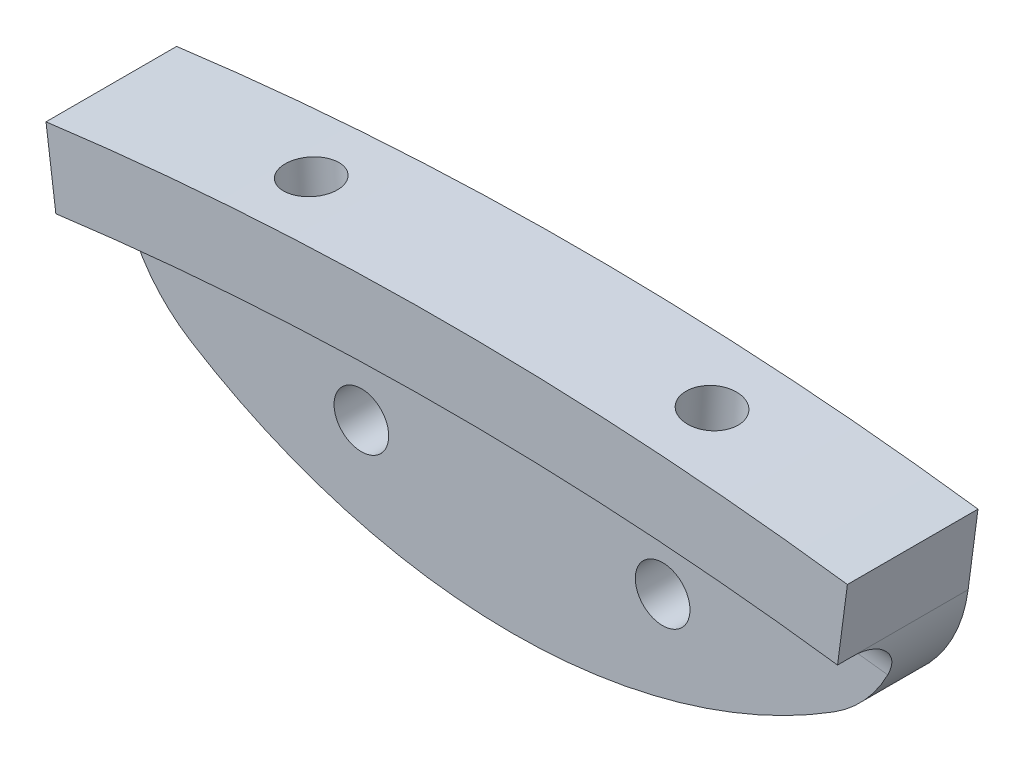
SolidWorks part; units mm, degrees
ref_plane "Front Plane" through (0, 0, 0) normal (0, 0, 1) x (1, 0, 0)
ref_plane "Top Plane" through (0, 0, 0) normal (0, 1, 0) x (1, 0, 0)
ref_plane "Right Plane" through (0, 0, 0) normal (1, 0, 0) x (0, 0, -1)
sketch "Sketch1" plane through (0, 0, 0) normal (0, 0, 1) x (1, 0, 0)
  line L0 (0, 0) -> (0, 193.675) construction
  line L1 (15.875, 0) -> (15.875, 193.675) construction
  line L2 (-15.875, 0) -> (-15.875, 193.675) construction
  line L3 (-25.3273, 192.0118) -> (-24.7044, 187.2902)
  line L4 (25.3273, 192.0118) -> (24.7044, 187.2902)
  line L5 (0, 188.9125) -> (0, 174.625) construction
  circle A0 centre (0, 0) radius 193.675 construction
  arc A1 (-25.3273, 192.0118) -> (25.3273, 192.0118) centre (0, 0) cw
  circle A2 centre (-9.5206, 181.5192) radius 1.7272
  circle A3 centre (9.5206, 181.5192) radius 1.7272
  arc A4 (-98.5088, 144.1871) -> (114.5348, 131.8168) centre (0, 0) cw construction
  arc A5 (-24.7044, 187.2902) -> (24.7044, 187.2902) centre (0, 0) cw construction
  arc A6 (-20.3182, 180.4641) -> (20.3182, 180.4641) centre (0, 212.8951) ccw
  arc A7 (-24.7044, 187.2902) -> (-20.3182, 180.4641) centre (-15.2612, 188.5358) ccw
  arc A8 (24.7044, 187.2902) -> (20.3182, 180.4641) centre (15.2612, 188.5358) cw
  arc A10 (-9.5206, 181.5192) -> (9.5206, 181.5192) centre (0, 0) cw construction
  point P19 (0, 181.7687)
  point P27 (-10.5513, 180.4641)
  dimension "D1" = 387.35
  dimension "D3" = 3.4544
  dimension "D4" = 19.05
  dimension "D7" = 4.7625
  dimension "D8" = 9.525
  dimension "D9" = 19.05
  dimension "D10" = 181.7687
  dimension "D2" = 50.8
  dimension "D5" = 15.875
  dimension "D6" = 15.875
extrude "Boss-Extrude1" add sketch "Sketch1" along normal blind 4.1275
sketch "Sketch2" plane through (0, 0, 4.1275) normal (0, 0, 1) x (1, 0, 0)
  line L0 (24.7044, 187.2902) -> (25.3273, 192.0118) construction
  line L1 (-25.3273, 192.0118) -> (-24.7044, 187.2902) construction
  line L2 (24.7044, 187.2902) -> (25.3273, 192.0118)
  line L3 (-25.3273, 192.0118) -> (-24.7044, 187.2902)
  arc A0 (25.3273, 192.0118) -> (-25.3273, 192.0118) centre (0, 0) ccw construction
  arc A1 (25.3273, 192.0118) -> (-25.3273, 192.0118) centre (0, 0) ccw
  arc A2 (-24.7044, 187.2902) -> (24.7044, 187.2902) centre (0, 0) cw
extrude "Boss-Extrude2" add sketch "Sketch2" along normal blind 4.1275
sketch "Sketch3" plane through (0, 0, 4.1275) normal (0, 0, 1) x (1, 0, 0)
  line L0 (-12.6909, 193.2588) -> (0, 0)
  line L1 (0, 0) -> (12.6909, 193.2588)
  arc A0 (25.3273, 192.0118) -> (-25.3273, 192.0118) centre (0, 0) ccw construction
  arc A1 (12.6909, 193.2588) -> (-12.6909, 193.2588) centre (0, 0) ccw
  dimension "D1" = 25.4
ref_plane "Plane2" through (-12.6909, 193.2588, 4.1275) normal (0.0655, -0.9979, 0) x (-0.9979, -0.0655, 0)
sketch "Sketch4" plane through (-12.6909, 193.2588, 4.1275) normal (0.0655, -0.9979, 0) x (-0.9979, -0.0655, 0)
  circle A0 centre (0, 0) radius 1.651
  dimension "D1" = 3.302
extrude "Cut-Extrude1" cut sketch "Sketch4" along normal offset from surface (4.6427 mm away) 0.127
pattern_circular "CirPattern1" count 2 every 7.5 about axis through (0, 0, 0) along (0, 0, 1) of "Cut-Extrude1"
fillet "Fillet1" radius 3.175 1 edges at (0, 188.9125, 4.1275)
